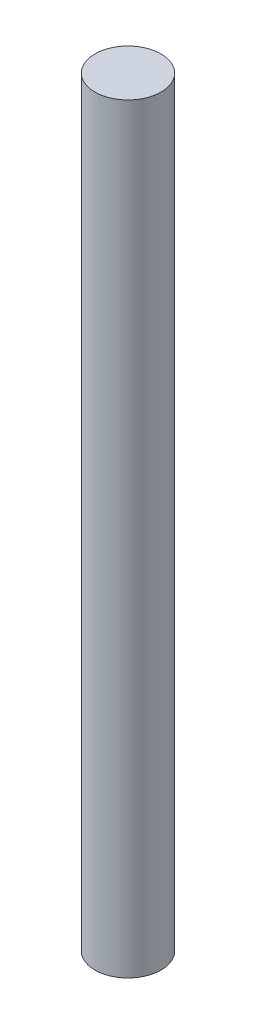
SolidWorks part; units mm, degrees
ref_plane "前视基准面" through (0, 0, 0) normal (0, 0, 1) x (1, 0, 0)
ref_plane "上视基准面" through (0, 0, 0) normal (0, 1, 0) x (1, 0, 0)
ref_plane "右视基准面" through (0, 0, 0) normal (1, 0, 0) x (0, 0, -1)
sketch "草图1" plane through (0, 0, 0) normal (0, 1, 0) x (1, 0, 0)
  circle A0 centre (0, 0) radius 10
  dimension "D1" = 20
extrude "凸台-拉伸1" add sketch "草图1" along normal blind 230
